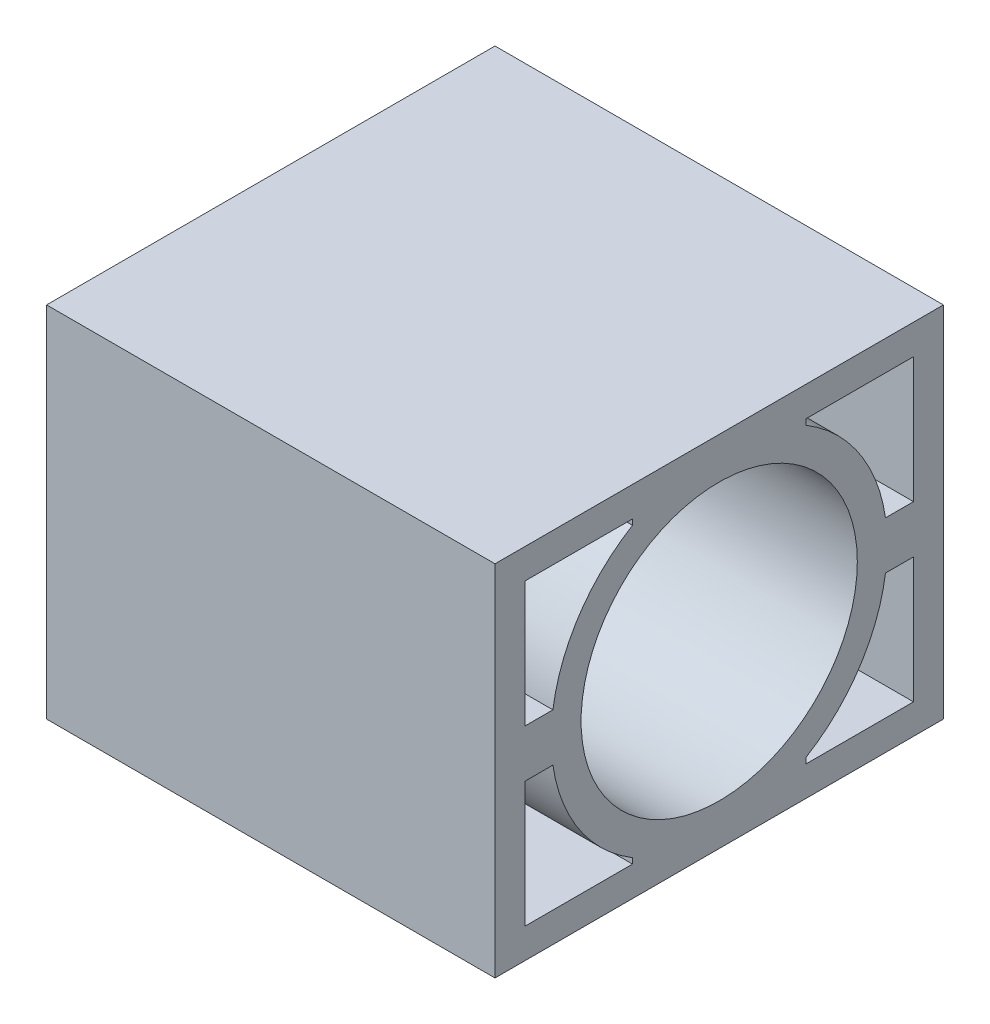
SolidWorks part; units mm, degrees
ref_plane "Front Plane" through (0, 0, 0) normal (0, 0, 1) x (1, 0, 0)
ref_plane "Top Plane" through (0, 0, 0) normal (0, 1, 0) x (1, 0, 0)
ref_plane "Right Plane" through (0, 0, 0) normal (1, 0, 0) x (0, 0, -1)
sketch "Sketch1" plane through (0, 0, 0) normal (1, 0, 0) x (0, 0, -1)
  line L1 (-37.5, 30) -> (37.5, 30)
  line L2 (-37.5, 30) -> (-37.5, -30)
  line L3 (-37.5, -30) -> (37.5, -30)
  line L4 (37.5, 30) -> (37.5, -30)
  line L5 (-37.5, 30) -> (37.5, -30) construction
  line L6 (-37.5, -30) -> (37.5, 30) construction
  point P0 (0, 0)
  dimension "D1" = 60
  dimension "D2" = 75
extrude "Boss-Extrude1" add sketch "Sketch1" along normal blind 75
sketch "Sketch2" plane through (75, 0, 0) normal (1, 0, 0) x (0, 0, -1)
  circle A4 centre (0, 0) radius 23.1
  dimension "D1" = 46.2
extrude "Cut-Extrude1" cut sketch "Sketch2" against normal blind 70
sketch "Sketch3" plane through (0, 0, 0) normal (-1, 0, 0) x (0, 0, 1)
  line L0 (0, 0) -> (-13.4, 0) construction
  line L1 (-5.0794, 12.4) -> (5.0794, 12.4)
  line L2 (-5.0794, -12.4) -> (5.0794, -12.4)
  line L3 (-12.3744, 12.3744) -> (0, 0) construction
  line L4 (-37.5, -30) -> (-37.5, 30) construction
  line L5 (32.5, -25) -> (14.5, -25)
  line L6 (32.5, -25) -> (32.5, -4)
  line L7 (32.5, 25) -> (14.5, 25)
  line L8 (-32.5, -25) -> (-32.5, -4)
  line L9 (32.5, -25) -> (-32.5, 25) construction
  line L10 (32.5, 25) -> (-32.5, -25) construction
  line L11 (-37.5, 30) -> (37.5, 30) construction
  line L12 (32.5, -4) -> (27.8138, -4)
  line L13 (14.5, -25) -> (14.5, -24.0699)
  line L14 (14.5, 25) -> (14.5, 24.0699)
  line L15 (32.5, 4) -> (27.8138, 4)
  line L16 (0, 0) -> (0, 30) construction
  line L17 (-14.5, -25) -> (-14.5, -24.0699)
  line L18 (-32.5, -4) -> (-27.8138, -4)
  line L19 (-32.5, 4) -> (-27.8138, 4)
  line L20 (-14.5, 25) -> (-14.5, 24.0699)
  line L21 (32.5, 4) -> (32.5, 25)
  line L22 (-14.5, -25) -> (-32.5, -25)
  line L23 (-32.5, 4) -> (-32.5, 25)
  line L24 (-14.5, 25) -> (-32.5, 25)
  arc A0 (-5.0794, 12.4) -> (-5.0794, -12.4) centre (0, 0) ccw
  arc A1 (5.0794, -12.4) -> (5.0794, 12.4) centre (0, 0) ccw
  circle A2 centre (-12.3744, 12.3744) radius 2.25
  circle A3 centre (12.3744, 12.3744) radius 2.25
  circle A4 centre (12.3744, -12.3744) radius 2.25
  circle A5 centre (-12.3744, -12.3744) radius 2.25
  arc A6 (27.8138, 4) -> (14.5, 24.0699) centre (0, 0) ccw
  circle A7 centre (0, 0) radius 23.1 construction
  arc A8 (14.5, -24.0699) -> (27.8138, -4) centre (0, 0) ccw
  arc A9 (-27.8138, -4) -> (-14.5, -24.0699) centre (0, 0) ccw
  arc A10 (-14.5, 24.0699) -> (-27.8138, 4) centre (0, 0) ccw
  point P18 (0, 0)
  point P35 (5.0596, -14.1017)
  point P37 (0, 0)
  dimension "D1" = 26.8
  dimension "D4" = 4.5
  dimension "D9" = 5
  dimension "D2" = 24.8
  dimension "D3" = 17.5
  dimension "D5" = 45
  dimension "D7" = 5
  dimension "D8" = 5
  dimension "D10" = 21
  dimension "D11" = 18
  dimension "D6" = 4
extrude "Cut-Extrude2" cut sketch "Sketch3" against normal through all
sketch "Sketch4" plane through (0, -30, 0) normal (0, -1, 0) x (1, 0, 0)
  line L0 (0, 0) -> (75, 0) construction
  line L1 (75, 37.5) -> (75, -37.5) construction
  line L2 (60, 27) -> (15, 27) construction
  line L3 (0, 37.5) -> (0, -37.5) construction
  circle A0 centre (60, 27) radius 2.25
  circle A1 centre (15, 27) radius 2.25
  circle A2 centre (60, -27) radius 2.25
  circle A3 centre (15, -27) radius 2.25
  dimension "D1" = 4.5
  dimension "D2" = 45
  dimension "D3" = 15
  dimension "D4" = 27
extrude "Cut-Extrude3" cut sketch "Sketch4" against normal up to next
